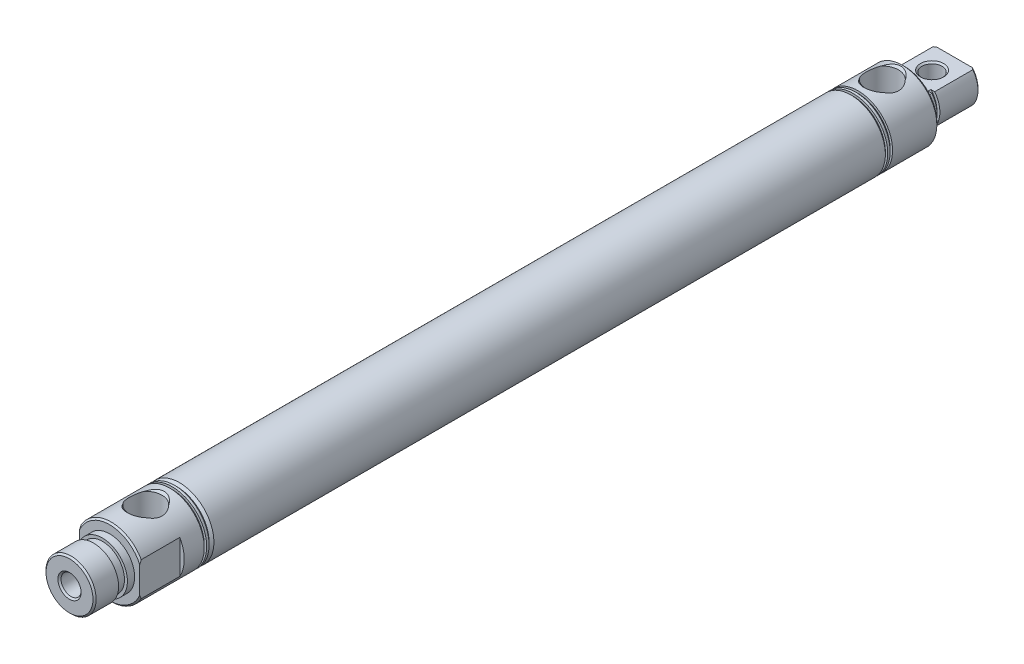
SolidWorks part; units mm, degrees
ref_plane "Front" through (0, 0, 0) normal (0, 0, 1) x (1, 0, 0)
ref_plane "Top" through (0, 0, 0) normal (0, 1, 0) x (1, 0, 0)
ref_plane "Right" through (0, 0, 0) normal (1, 0, 0) x (0, 0, -1)
sketch "Sketch1" plane through (0, 0, 0) normal (0, 0, 1) x (1, 0, 0)
  circle A0 centre (0, 0) radius 10.922
  dimension "E" = 21.844
extrude "Extrude1" add sketch "Sketch1" along normal up to surface (133.731 mm away) and the other way up to surface (133.731 mm away)
ref_plane "SwitchPlaneA" through (0, 0, 95.879) normal (0, 0, 1) x (1, 0, 0)
ref_plane "SwitchPlaneB" through (0, 0, -82.769) normal (0, 0, -1) x (-1, 0, 0)
sketch "Sketch2" plane through (0, 0, 0) normal (1, 0, 0) x (0, 0, -1)
  line L0 (0, 0) -> (-79.7053, 0) construction
  line L1 (-133.731, 7.9248) -> (-136.017, 7.9248)
  line L2 (-133.731, 10.922) -> (-133.731, -10.922) construction
  line L3 (-136.017, 7.9248) -> (-136.017, 7)
  line L4 (-138.817, 7.9375) -> (-146.431, 7.9375)
  line L5 (-146.431, 7.9375) -> (-146.431, 0)
  line L6 (-146.431, 0) -> (-133.731, 0)
  line L7 (-133.731, 0) -> (-133.731, 7.9248)
  line L8 (-138.817, 7.9375) -> (-138.817, 7)
  line L9 (-138.817, 7) -> (-136.017, 7)
  dimension "D1" = 2.286
  dimension "NN" = 15.875
  dimension "B" = 15.8496
  dimension "D2" = 14
  dimension "W-K" = 12.7
  dimension "D3" = 2.8
revolve "Nose" add sketch "Sketch2" angle 360 about L0
sketch "Sketch3" plane through (0, 0, 0) normal (1, 0, 0) x (0, 0, -1)
  line L0 (0, 0) -> (-66.9635, 0) construction
  line L1 (133.731, 10.922) -> (-133.731, 10.922) construction
  line L2 (-114.681, 10.922) -> (-113.919, 10.922)
  line L3 (-114.681, 10.922) -> (-114.681, 10.16)
  line L4 (-114.681, 10.16) -> (-113.919, 10.16)
  line L5 (-113.919, 10.922) -> (-113.919, 10.16)
  line L6 (-113.157, 10.922) -> (-113.157, 10.16)
  line L7 (-113.157, 10.16) -> (-112.395, 10.16)
  line L8 (-112.395, 10.16) -> (-111.633, 10.922)
  line L9 (-111.633, 10.922) -> (-113.157, 10.922)
  line L10 (103.207, 10.922) -> (103.207, 10.16)
  line L11 (103.207, 10.16) -> (102.445, 10.922)
  line L12 (102.445, 10.922) -> (103.207, 10.922)
  line L13 (101.683, 10.922) -> (101.683, 10.16)
  line L14 (101.683, 10.16) -> (100.921, 10.922)
  line L15 (100.921, 10.922) -> (101.683, 10.922)
  line L16 (-133.731, 10.922) -> (-133.731, -10.922) construction
  line L17 (133.731, -10.922) -> (133.731, 10.922) construction
  dimension "D1" = 0.762
  dimension "D2" = 30.524
  dimension "D3" = 19.05
  dimension "D4" = 0.762
  dimension "D5" = 45
  dimension "D6" = 1.524
  dimension "D7" = 0.762
revolve "CoverGrooves" cut sketch "Sketch3" angle 360 about L0
sketch "Sketch7" plane through (0, 0, 0) normal (1, 0, 0) x (0, 0, -1)
  line L0 (-122.301, 0) -> (-122.301, 19.911) construction
  line L1 (-122.301, 10.922) -> (-116.451, 10.922)
  line L2 (-114.681, 10.922) -> (-133.731, 10.922) construction
  line L3 (-116.451, 10.922) -> (-117.151, 10.222)
  line L4 (-117.151, 10.222) -> (-117.151, 0)
  line L5 (-117.151, 0) -> (-122.301, 0)
  line L6 (-122.301, 0) -> (-122.301, 10.922)
  line L7 (-146.431, 7.9375) -> (-146.431, -7.9375) construction
  line L8 (-111.633, 10.922) -> (-112.395, 10.16) construction
  dimension "D1" = 10.3
  dimension "D2" = 0.7
  dimension "Y-K" = 24.13
revolve "FrontPort" cut sketch "Sketch7" angle 360 about L0
sketch "Sketch8" plane through (0, 0, 146.431) normal (0, 0, 1) x (1, 0, 0)
  circle A0 centre (0, 0) radius 3.175
  dimension "MM" = 6.35
extrude "RodHole" cut sketch "Sketch8" against normal up to surface (237.831 mm away)
sketch "Sketch9" plane through (0, 0, -91.4) normal (0, 0, 1) x (1, 0, 0)
  circle A0 centre (0, 0) radius 9.525
  dimension "Bore" = 19.05
extrude "StrokeChamber" cut sketch "Sketch9" along normal up to surface (182.8 mm away)
chamfer "Chamfer1" distance 0.5 angle 45 4 edges at (10.922, 0, -133.731) (10.922, 0, 133.731) (-7.9375, 0, 146.431) (3.175, 0, 146.431)
sketch "Sketch4" plane through (0, 0, 0) normal (0, 1, 0) x (1, 0, 0)
  line L0 (0, 0) -> (0, 54.4802) construction
  line L2 (10.922, -133.731) -> (9.525, -133.731)
  line L3 (10.922, -133.731) -> (10.922, -121.031)
  line L4 (10.922, -121.031) -> (9.525, -121.031)
  line L5 (9.525, -133.731) -> (9.525, -121.031)
  line L6 (10.922, 130.683) -> (10.422, 130.683)
  line L7 (10.922, 130.683) -> (10.922, 133.731)
  line L8 (10.922, 133.731) -> (10.422, 133.731)
  line L9 (10.422, 130.683) -> (10.422, 133.731)
  line L10 (-10.922, 0) -> (10.922, 0) construction
  line L11 (-10.922, -133.731) -> (10.922, -133.731) construction
  line L12 (10.922, 133.731) -> (-10.922, 133.731) construction
  line L13 (-10.422, 130.683) -> (-10.422, 133.731)
  line L14 (-10.922, 133.731) -> (-10.422, 133.731)
  line L15 (-10.922, 130.683) -> (-10.922, 133.731)
  line L16 (-10.922, 130.683) -> (-10.422, 130.683)
  line L17 (-9.525, -133.731) -> (-9.525, -121.031)
  line L18 (-10.922, -121.031) -> (-9.525, -121.031)
  line L19 (-10.922, -133.731) -> (-10.922, -121.031)
  line L20 (-10.922, -133.731) -> (-9.525, -133.731)
  line L21 (-10.922, 0) -> (10.922, 0) construction
  dimension "D1" = 12.7
  dimension "NC" = 20.844
  dimension "N" = 19.05
  dimension "NE" = 3.048
extrude "Flats" cut sketch "Sketch4" against normal through all and the other way through all
sketch "Sketch10" [suppressed] plane through (0, 0, 0) normal (1, 0, 0) x (0, 0, -1)
  line L0 (0, 0) -> (-22.9719, 0) construction
  line L1 (200.152, 0) -> (200.152, 5.85)
  line L2 (200.152, 5.85) -> (199.452, 5.15)
  line L3 (199.452, 5.15) -> (0, 5.15)
  line L4 (0, 5.15) -> (0, 0)
  line L5 (0, 0) -> (200.152, 0)
  line L6 (-178.054, 10.922) -> (-178.816, 10.16) construction
  line L8 (200.152, -10.922) -> (200.152, 10.922) construction
  dimension "D1" = 10.3
  dimension "D2" = 0.7
revolve "RearStdPort" [suppressed] cut sketch "Sketch10" angle 360 about L0
sketch "Sketch11" plane through (0, 0, 0) normal (1, 0, 0) x (0, 0, -1)
  line L0 (0, 0) -> (65.1253, 0) construction
  line L1 (133.731, 7.4375) -> (133.231, 7.9375)
  line L2 (133.231, 7.9375) -> (121.17, 7.9375)
  line L3 (121.17, 7.9375) -> (121.17, 7)
  line L4 (121.17, 7) -> (120.269, 7)
  line L5 (120.269, 7) -> (120.269, 7.9375)
  line L6 (120.269, 7.9375) -> (117.983, 7.9375)
  line L7 (117.983, 7.9375) -> (117.983, 10.16)
  line L8 (117.983, 10.16) -> (117.221, 10.922)
  line L9 (100.921, 10.922) -> (-111.633, 10.922) construction
  line L10 (117.221, 10.922) -> (133.731, 10.922)
  line L11 (133.731, 7.4375) -> (133.731, 10.922)
  line L16 (103.207, 10.16) -> (102.445, 10.922) construction
  line L17 (133.731, -10.922) -> (133.731, 10.922) construction
  dimension "D1" = 0.901
  dimension "D2" = 2.286
  dimension "D3" = 15.875
  dimension "ZB-LB+L" = 15.748
  dimension "D4" = 14
revolve "EndThreads" cut sketch "Sketch11" angle 360 about L0
sketch "Sketch13" plane through (0, 0, 0) normal (1, 0, 0) x (0, 0, -1)
  line L0 (110.871, 0) -> (110.871, 52.324) construction
  line L1 (110.871, 0) -> (116.021, 0)
  line L2 (116.021, 0) -> (116.021, 10.222)
  line L3 (116.021, 10.222) -> (116.721, 10.922)
  line L5 (116.721, 10.922) -> (110.871, 10.922)
  line L6 (110.871, 10.922) -> (110.871, 0)
  line L10 (133.731, -7.4375) -> (133.731, 7.4375) construction
  line L11 (-111.633, 10.922) -> (-113.157, 10.922) construction
  line L12 (-117.151, 0) -> (-122.301, 0) construction
  line L13 (-116.451, 10.922) -> (-117.151, 10.222) construction
  dimension "D1" = 22.86
revolve "RearTopPort" cut sketch "Sketch13" angle 360 about L0
sketch "Sketch12" plane through (0, 0, 0) normal (1, 0, 0) x (0, -1, 0)
  line L0 (0, 0) -> (0, 62.5586) construction
  line L1 (7.4375, 133.731) -> (-7.4375, 133.731) construction
  line L2 (10.922, 133.731) -> (4.826, 133.731)
  line L3 (10.922, 133.731) -> (10.922, 118.707)
  line L4 (10.922, 118.707) -> (4.826, 118.707)
  line L5 (4.826, 133.731) -> (4.826, 118.707)
  line L6 (-10.922, 0) -> (10.922, 0) construction
  line L7 (-4.826, 133.731) -> (-4.826, 118.707)
  line L8 (-10.922, 118.707) -> (-4.826, 118.707)
  line L9 (-10.922, 133.731) -> (-10.922, 118.707)
  line L10 (-10.922, 133.731) -> (-4.826, 133.731)
  line L12 (-10.922, 0) -> (10.922, 0) construction
  dimension "D1" = 15.024
  dimension "F" = 9.652
extrude "EndFlats" cut sketch "Sketch12" against normal through all and the other way through all
sketch "Sketch15" plane through (0, 0, 0) normal (1, 0, 0) x (0, -1, 0)
  line L0 (0, 126.619) -> (21.0846, 126.619) construction
  line L1 (4.826, 130.3067) -> (4.326, 129.8067)
  line L2 (4.826, 133.231) -> (4.826, 121.17) construction
  line L3 (4.326, 129.8067) -> (-4.326, 129.8067)
  line L4 (-4.326, 129.8067) -> (-4.826, 130.3067)
  line L5 (-4.826, 121.17) -> (-4.826, 133.231) construction
  line L6 (-4.826, 130.3067) -> (-4.826, 126.619)
  line L7 (-4.826, 126.619) -> (4.826, 126.619)
  line L8 (4.826, 126.619) -> (4.826, 130.3067)
  line L9 (10.16, 117.983) -> (-10.16, 117.983) construction
  dimension "D1" = 0.5
  dimension "G" = 6.3754
  dimension "L" = 8.636
revolve "ClevisPinHole" cut sketch "Sketch15" angle 360 about L0
sketch "Sketch18" plane through (0, 0, 0) normal (1, 0, 0) x (0, 0, -1)
  line L0 (126.619, 0) -> (126.619, 25.8254) construction
  line L2 (126.619, 0) -> (126.619, -21.0846) construction
  line L3 (126.619, 9.525) -> (129.3067, 9.525)
  line L4 (129.3067, 9.525) -> (129.8067, 9.025)
  line L5 (129.8067, 9.025) -> (129.8067, -9.025)
  line L6 (129.8067, -9.025) -> (129.3067, -9.525)
  line L7 (129.3067, -9.525) -> (126.619, -9.525)
  line L8 (126.619, -9.525) -> (126.619, 9.525)
  line L9 (129.8067, -4.326) -> (129.8067, 4.326) construction
  point P13 (126.619, 0)
  dimension "D1" = 0.5
  dimension "GB" = 19.05
revolve "ClevisPin" [suppressed] add sketch "Sketch18" angle 360 about L0
ref_plane "Plane1" through (0, 10.222, 0) normal (0, 1, 0) x (-1, 0, 0)
